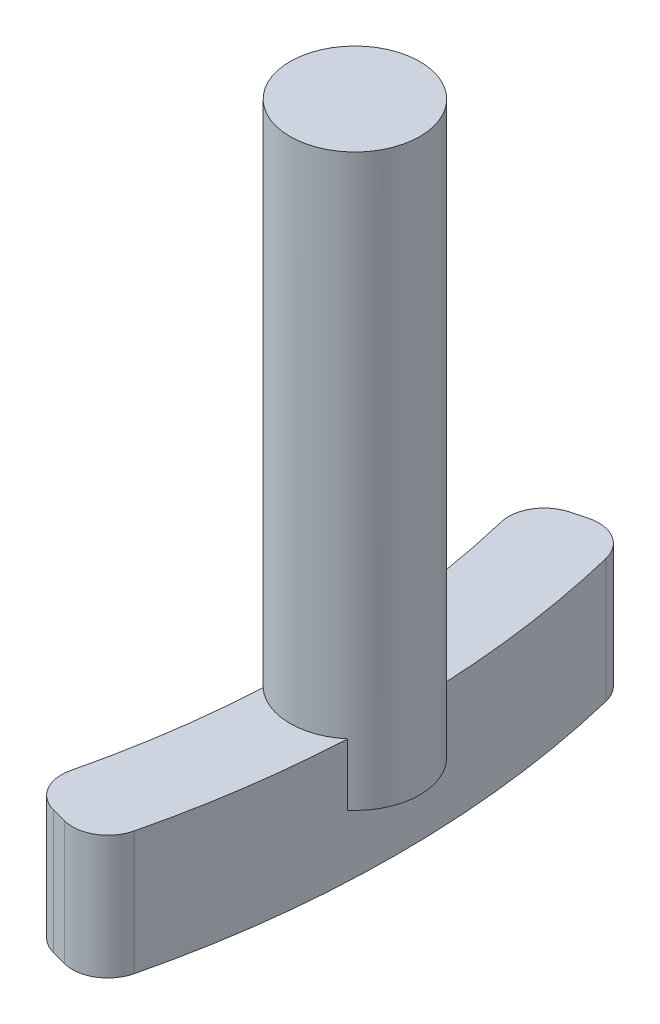
SolidWorks part; units mm, degrees
material "ABS"
ref_plane "Front Plane" through (0, 0, 0) normal (0, 0, 1) x (1, 0, 0)
ref_plane "Top Plane" through (0, 0, 0) normal (0, 1, 0) x (1, 0, 0)
ref_plane "Right Plane" through (0, 0, 0) normal (1, 0, 0) x (0, 0, -1)
sketch "Эскиз1" plane through (0, 0, 0) normal (0, 1, 0) x (1, 0, 0)
  line L6 (-0.9789, -8.3427) -> (-0.4958, -8.4721)
  line L7 (-0.9789, 8.3427) -> (-0.4958, 8.4721)
  arc A18 (0.9195, -7.6322) -> (-0.4958, -8.4721) centre (-0.1981, -7.3613) cw
  arc A19 (0.9195, -7.6322) -> (0.9195, 7.6322) centre (-30.5687, 0) ccw
  arc A20 (-0.4958, 8.4721) -> (0.9195, 7.6322) centre (-0.1981, 7.3613) cw
  arc A21 (-0.9789, 8.3427) -> (-1.799, 6.9614) centre (-0.6813, 7.2319) ccw
  arc A22 (-1.799, -6.9614) -> (-1.799, 6.9614) centre (-30.5687, 0) ccw
  arc A23 (-0.9789, -8.3427) -> (-1.799, -6.9614) centre (-0.6813, -7.2319) cw
  point P13 (0.3409, 8.2822)
  point P30 (0.3409, 8.2822)
  point P31 (0.3409, -8.2822)
extrude "Бобышка-Вытянуть1" add sketch "Эскиз1" along normal blind 4
ref_plane "Плоскость1" through (0, 2, 0) normal (0, 1, 0) x (1, 0, 0)
sketch "Эскиз2" plane through (0, 2, 0) normal (0, 1, 0) x (1, 0, 0)
  circle A2 centre (0.4313, 0) radius 2.1
  dimension "D1" = 4.2
extrude "Бобышка-Вытянуть2" add sketch "Эскиз2" along normal blind 18.44
